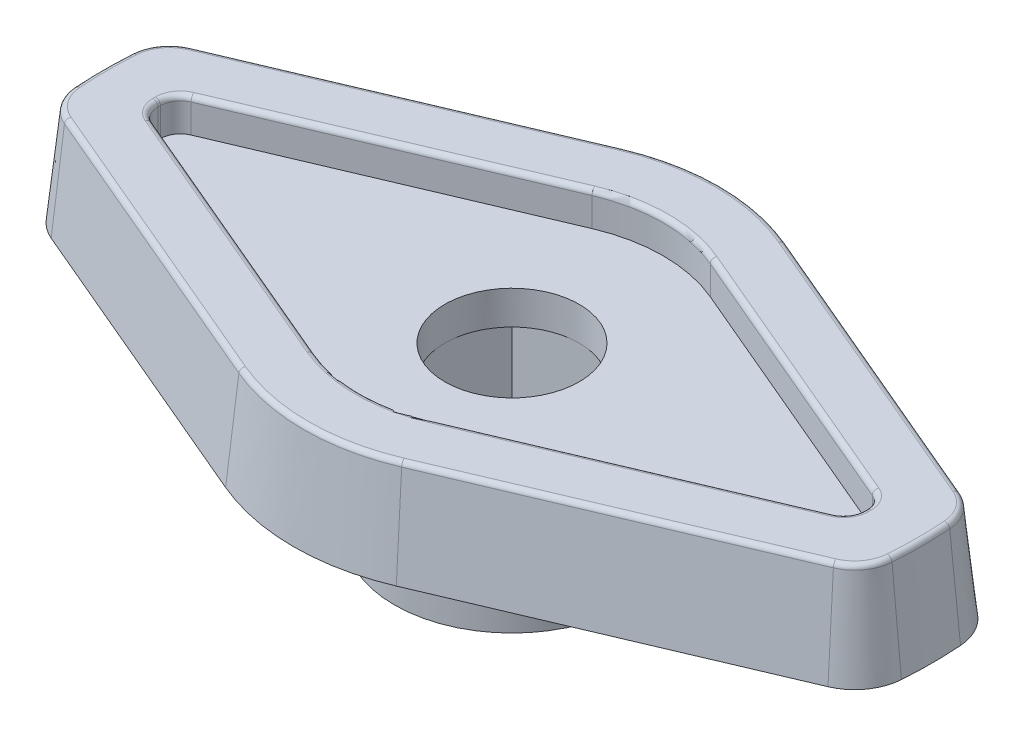
SolidWorks part; units mm, degrees
ref_plane "Front Plane" through (0, 0, 0) normal (0, 0, 1) x (1, 0, 0)
ref_plane "Top Plane" through (0, 0, 0) normal (0, 1, 0) x (1, 0, 0)
ref_plane "Right Plane" through (0, 0, 0) normal (1, 0, 0) x (0, 0, -1)
sketch "Sketch1" plane through (0, 0, 0) normal (0, 1, 0) x (1, 0, 0)
  line L0 (13, 0) -> (25, 0) construction
  line L1 (0, 0) -> (0, 13) construction
  line L2 (5.0795, 11.9666) -> (23.1176, 4.3098)
  line L3 (5.0795, -11.9666) -> (23.1176, -4.3098)
  line L4 (-5.0795, -11.9666) -> (-23.1176, -4.3098)
  line L5 (-5.0795, 11.9666) -> (-23.1176, 4.3098)
  arc A0 (5.0795, 11.9666) -> (-5.0795, 11.9666) centre (0, 0) ccw
  arc A1 (24.938, -1.7594) -> (24.938, 1.7594) centre (0, 0) ccw
  arc A2 (-24.938, 1.7594) -> (-24.938, -1.7594) centre (0, 0) ccw
  arc A3 (-5.0795, -11.9666) -> (5.0795, -11.9666) centre (0, 0) ccw
  arc A4 (23.1176, -4.3098) -> (24.938, -1.7594) centre (21.9454, -1.5483) ccw
  arc A5 (23.1176, 4.3098) -> (24.938, 1.7594) centre (21.9454, 1.5483) cw
  arc A6 (-23.1176, -4.3098) -> (-24.938, -1.7594) centre (-21.9454, -1.5483) cw
  arc A7 (-23.1176, 4.3098) -> (-24.938, 1.7594) centre (-21.9454, 1.5483) ccw
  point P15 (24.7361, -3.6228)
  point P18 (24.7361, 3.6228)
  point P21 (-24.7361, -3.6228)
  point P24 (-24.7361, 3.6228)
  dimension "D4" = 3
  dimension "D1" = 25
  dimension "D2" = 13
  dimension "D3" = 23
extrude "Boss-Extrude1" add sketch "Sketch1" along normal blind 6 draft 6
sketch "Sketch2" plane through (0, 6, 0) normal (0, 1, 0) x (1, 0, 0)
  line L0 (0, 0) -> (21, 0) construction
  line L1 (0, 0) -> (0, 9) construction
  line L2 (3.5166, 8.2845) -> (20.9819, 0.8709)
  line L3 (22.8712, 3.7293) -> (4.8331, 11.3861) construction
  line L4 (3.5166, -8.2845) -> (20.9819, -0.8709)
  line L5 (-3.5166, -8.2845) -> (-20.9819, -0.8709)
  line L6 (-3.5166, 8.2845) -> (-20.9819, 0.8709)
  arc A0 (3.5166, 8.2845) -> (-3.5166, 8.2845) centre (0, 0) ccw
  arc A1 (-20.9819, 0.8709) -> (-20.9819, -0.8709) centre (0, 0) ccw
  arc A2 (20.9819, -0.8709) -> (20.9819, 0.8709) centre (0, 0) ccw
  arc A3 (-3.5166, -8.2845) -> (3.5166, -8.2845) centre (0, 0) ccw
  dimension "D1" = 21
  dimension "D2" = 9
extrude "Cut-Extrude1" cut sketch "Sketch2" against normal blind 2
fillet "Fillet1" radius 1.2 4 edges at (-20.9819, 5, -0.8709) (-20.9819, 5, 0.8709) (20.9819, 5, -0.8709) (20.9819, 5, 0.8709)
fillet "Fillet2" radius 0.3 24 edges at (13.8522, 6, 7.5577) (0, 6, 12.3694) (-13.8522, 6, 7.5577) (-23.874, 6, 2.9248) (-24.3694, 6, 0) (-23.874, 6, -2.9248) (-13.8522, 6, -7.5577) (0, 6, -12.3694) (13.8522, 6, -7.5577) (23.874, 6, -2.9248) (24.3694, 6, 0) (23.874, 6, 2.9248) (-11.8927, 6, -4.7291) (-20.7994, 6, -0.7331) (-21, 6, 0) (-20.7994, 6, 0.7331) (-11.8927, 6, 4.7291) (0, 6, 9) (11.8927, 6, 4.7291) (20.7994, 6, 0.7331) (21, 6, 0) (20.7994, 6, -0.7331) (11.8927, 6, -4.7291) (0, 6, -9)
sketch "Sketch3" plane through (0, 0, 0) normal (0, -1, 0) x (1, 0, 0)
  circle A0 centre (0, 0) radius 7
  dimension "D1" = 14
extrude "Boss-Extrude2" add sketch "Sketch3" along normal blind 6
fillet "Fillet3" radius 1 1 edges at (0, 0, 7)
sketch "Sketch4" plane through (0, -6, 0) normal (0, -1, 0) x (1, 0, 0)
  circle A0 centre (0, 0) radius 4
  dimension "D1" = 8
extrude "Cut-Extrude2" cut sketch "Sketch4" against normal through all
sketch "Sketch5" plane through (0, -6, 0) normal (0, -1, 0) x (1, 0, 0)
  line L1 (4, -4) -> (-4, -4)
  line L2 (4, -4) -> (4, 4)
  line L3 (4, 4) -> (-4, 4)
  line L4 (-4, -4) -> (-4, 4)
  line L5 (4, -4) -> (-4, 4) construction
  line L6 (4, 4) -> (-4, -4) construction
  point P0 (0, 0)
  dimension "D1" = 8
  dimension "D2" = 8
extrude "Cut-Extrude3" cut sketch "Sketch5" against normal blind 8
sketch "Sketch6" plane through (0, -6, 0) normal (0, -1, 0) x (1, 0, 0)
  circle A0 centre (0, 0) radius 6
  dimension "D1" = 12
extrude "Cut-Extrude4" cut sketch "Sketch6" against normal blind 2
